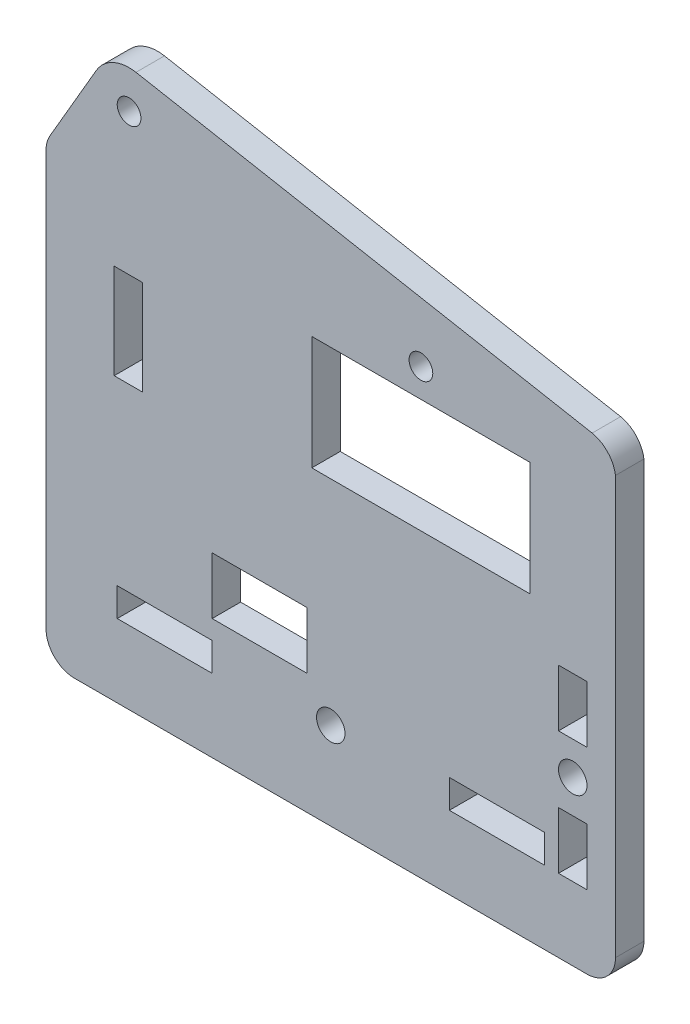
SolidWorks part; units mm, degrees
ref_plane "前基準面" through (0, 0, 0) normal (0, 0, 1) x (1, 0, 0)
ref_plane "上基準面" through (0, 0, 0) normal (0, 1, 0) x (1, 0, 0)
ref_plane "右基準面" through (0, 0, 0) normal (1, 0, 0) x (0, 0, -1)
sketch "草圖1" plane through (0, 0, 0) normal (0, 0, 1) x (1, 0, 0)
  line L0 (102.1766, 125.6999) -> (99.1766, 125.7) construction
  line L1 (102.1766, 135.6999) -> (102.1766, 125.6999) construction
  line L2 (99.1766, 135.7) -> (102.1766, 135.6999) construction
  line L3 (99.1766, 125.7) -> (99.1766, 135.7) construction
  line L4 (149.5459, 145.6497) -> (101.4755, 154.5381) construction
  line L5 (102.1766, 125.6999) -> (99.1766, 125.7)
  line L6 (102.1766, 135.6999) -> (102.1766, 125.6999)
  line L7 (99.1766, 135.7) -> (102.1766, 135.6999)
  line L8 (99.1766, 125.7) -> (99.1766, 135.7)
  line L9 (149.5459, 145.6497) -> (101.4755, 154.5381)
  line L10 (95.0002, 96) -> (149.0002, 95.9997)
  line L11 (120.0004, 139.6999) -> (143.0003, 139.6999)
  line L12 (120.0004, 139.6999) -> (120.0004, 127.6997)
  line L13 (120.0004, 127.6997) -> (143.0003, 127.6997)
  line L14 (143.0003, 139.6999) -> (143.0003, 127.6997)
  line L15 (146.0003, 122.6997) -> (149.0003, 122.6997)
  line L16 (146.0003, 122.6997) -> (146.0003, 116.6997)
  line L17 (146.0003, 116.6997) -> (149.0003, 116.6997)
  line L18 (149.0003, 122.6997) -> (149.0003, 116.6997)
  line L19 (134.5002, 106.6998) -> (144.5002, 106.6998)
  line L20 (134.5002, 106.6998) -> (134.5002, 103.6997)
  line L21 (134.5002, 103.6997) -> (144.5002, 103.6997)
  line L22 (144.5002, 106.6998) -> (144.5002, 103.6997)
  line L23 (146.0002, 109.6997) -> (149.0002, 109.6997)
  line L24 (146.0002, 109.6997) -> (146.0002, 103.6997)
  line L25 (146.0002, 103.6997) -> (149.0002, 103.6997)
  line L26 (149.0002, 109.6997) -> (149.0002, 103.6997)
  line L27 (109.5002, 114.6999) -> (119.5002, 114.6999)
  line L28 (109.5002, 114.6999) -> (109.5002, 108.6999)
  line L29 (109.5002, 108.6999) -> (119.5002, 108.6999)
  line L30 (119.5002, 114.6999) -> (119.5002, 108.6999)
  line L31 (99.5002, 106.7) -> (109.5002, 106.7)
  line L32 (99.5002, 106.7) -> (99.5002, 103.6999)
  line L33 (99.5002, 103.6999) -> (109.5002, 103.6999)
  line L34 (109.5002, 106.7) -> (109.5002, 103.6999)
  line L35 (152.0004, 98.9997) -> (152.0011, 143.0137)
  line L36 (92.0004, 142.7) -> (92.0003, 99)
  line L37 (97.2893, 152.6138) -> (92.4063, 144.2068)
  circle A0 centre (131.5006, 142.6998) radius 1.25 construction
  circle A1 centre (147.5003, 113.1997) radius 1.5 construction
  circle A2 centre (122.0003, 105.1998) radius 1.5 construction
  circle A3 centre (100.7481, 150.6048) radius 1.25 construction
  arc A4 (101.4755, 154.5381) -> (97.2893, 152.6138) centre (100.7482, 150.6047) ccw construction
  arc A5 (152.0011, 143.0137) -> (149.5459, 145.6497) centre (148.8904, 142.5777) ccw construction
  arc A6 (149.0002, 95.9997) -> (152.0004, 98.9997) centre (149.0002, 98.9999) ccw construction
  arc A7 (92.0003, 99) -> (95.0002, 96) centre (95.0003, 99) ccw construction
  circle A8 centre (131.5006, 142.6998) radius 1.25
  circle A9 centre (147.5003, 113.1997) radius 1.5
  circle A10 centre (122.0003, 105.1998) radius 1.5
  circle A11 centre (100.7481, 150.6048) radius 1.25
  arc A12 (101.4755, 154.5381) -> (97.2893, 152.6138) centre (100.7482, 150.6047) ccw
  arc A13 (152.0011, 143.0137) -> (149.5459, 145.6497) centre (148.8904, 142.5777) ccw
  arc A14 (149.0002, 95.9997) -> (152.0004, 98.9997) centre (149.0002, 98.9999) ccw
  arc A15 (92.0003, 99) -> (95.0002, 96) centre (95.0003, 99) ccw
  arc A16 (92.4063, 144.2068) -> (92.0004, 142.7) centre (95.0008, 142.6998) ccw construction
  arc A17 (92.4063, 144.2068) -> (92.0004, 142.7) centre (95.0008, 142.6998) ccw
  point P0 (131.5003, 124.6998)
  point P2 (102.1766, 125.6999)
extrude "填料-伸長1" add sketch "草圖1" along normal blind 3
